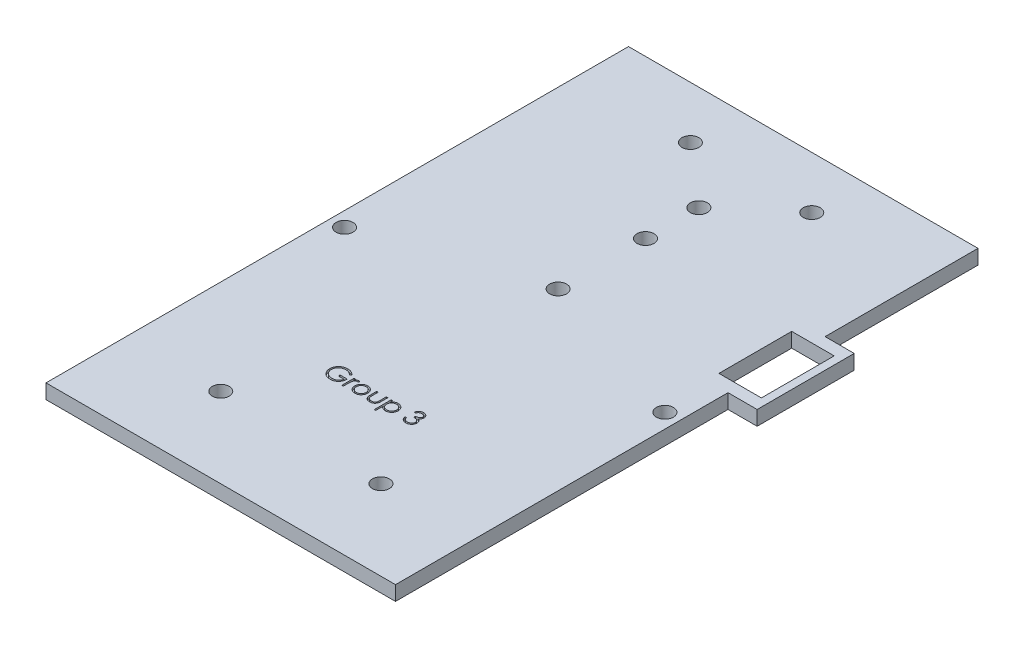
SolidWorks part; units mm, degrees
material "Acrylic (Medium-high impact)"
ref_plane "Front Plane" through (0, 0, 0) normal (0, 0, 1) x (1, 0, 0)
ref_plane "Top Plane" through (0, 0, 0) normal (0, 1, 0) x (1, 0, 0)
ref_plane "Right Plane" through (0, 0, 0) normal (1, 0, 0) x (0, 0, -1)
sketch "Sketch1" plane through (0, 0, 0) normal (0, 1, 0) x (1, 0, 0)
  line L0 (0, 0) -> (0, 50000) construction
  line L1 (36, -60) -> (-36, -60)
  line L2 (36, -60) -> (36, 60)
  line L3 (36, 60) -> (-36, 60)
  line L4 (-36, -60) -> (-36, 60)
  line L5 (36, -60) -> (-36, 60) construction
  line L6 (36, 60) -> (-36, -60) construction
  line L7 (0, 18.5) -> (36, 18.5) construction
  line L8 (0, 9.5) -> (0, -1.5)
  line L9 (0, 0) -> (50000, 0) construction
  line L10 (-20.7309, 49.25) -> (20.7309, 49.25) construction
  line L11 (30, 8.5) -> (42, 8.5)
  line L12 (30, 8.5) -> (30, 28.5)
  line L13 (30, 28.5) -> (42, 28.5)
  line L14 (42, 8.5) -> (42, 28.5)
  line L15 (30, 8.5) -> (42, 28.5) construction
  line L16 (30, 28.5) -> (42, 8.5) construction
  line L17 (40.375, 11) -> (31.625, 11)
  line L18 (40.375, 11) -> (40.375, 26)
  line L19 (40.375, 26) -> (31.625, 26)
  line L20 (31.625, 11) -> (31.625, 26)
  line L21 (40.375, 11) -> (31.625, 26) construction
  line L22 (40.375, 26) -> (31.625, 11) construction
  circle A0 centre (-33, -1.5) radius 1.75
  circle A1 centre (33, -1.5) radius 1.75
  circle A2 centre (-16.5, -43.5) radius 1.75
  circle A3 centre (16.5, -43.5) radius 1.75
  circle A4 centre (0, 27.5) radius 1.75
  circle A5 centre (0, 9.5) radius 1.75
  circle A10 centre (0, 38.5) radius 1.75
  circle A11 centre (0, 38.5) radius 1.75 construction
  circle A12 centre (-12.5, 49.25) radius 1.75
  circle A13 centre (12.5, 49.25) radius 1.75
  point P0 (0, 0)
  point P29 (36, 0)
  point P32 (36, 18.5)
  point P44 (0, 60)
  point P45 (0, 38.5)
  point P46 (0, 49.25)
  point P48 (0, 38.5)
  point P52 (0, 49.25)
  dimension "D3" = 3.5
  dimension "D4" = 3.5
  dimension "D5" = 33
  dimension "D6" = 3.5
  dimension "D7" = 3.5
  dimension "D10" = 3.5
  dimension "D11" = 3.5
  dimension "D15" = 20
  dimension "D16" = 12
  dimension "D17" = 15
  dimension "D19" = 66
  dimension "D12" = 9
  dimension "D20" = 3.5
  dimension "D21" = 3.5
  dimension "D1" = 120
  dimension "D2" = 72
  dimension "D8" = 42
  dimension "D9" = 16.5
  dimension "D13" = 18
  dimension "D14" = 11
  dimension "D18" = 8.75
  dimension "D22" = 25
extrude "Boss-Extrude1" add sketch "Sketch1" along normal blind 3
sketch "Sketch2" plane through (0, 3, 0) normal (0, 1, 0) x (1, 0, 0)
  line L0 (-36, -30) -> (36, -30) construction
  line L1 (-36, -60) -> (-36, 60) construction
  line L2 (36, -60) -> (36, 8.5) construction
  line L3 (36, -60) -> (-36, -60) construction
  text T0 "Group 3"
  dimension "D1" = 30
extrude "Cut-Extrude1" cut sketch "Sketch2" against normal blind 0.5
